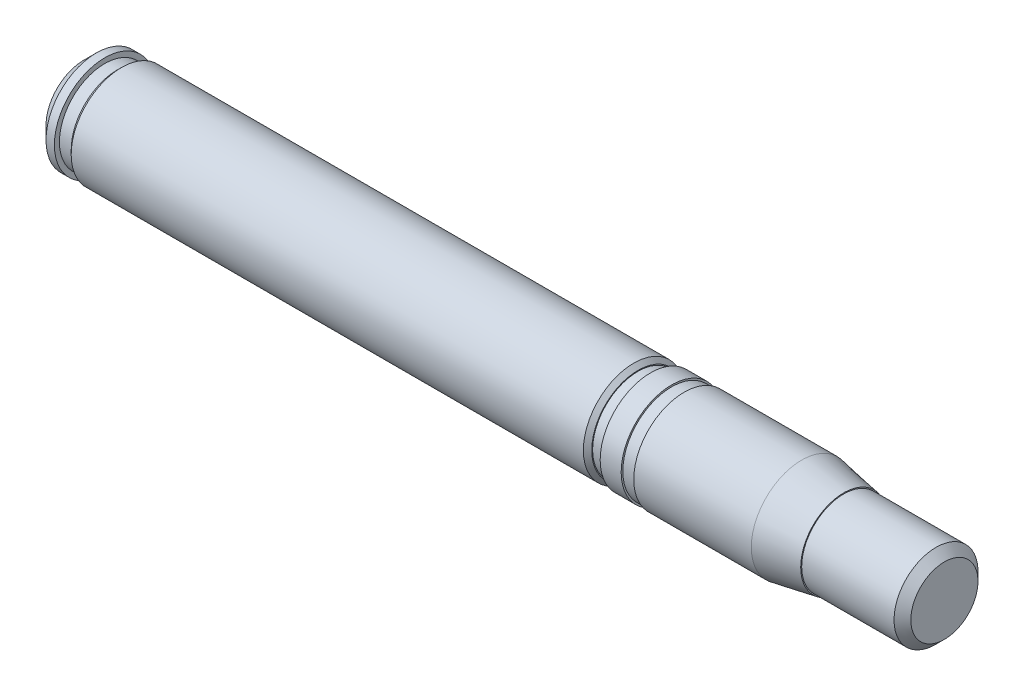
SolidWorks part; units mm, degrees
ref_plane "Plan de face" through (0, 0, 0) normal (0, 0, 1) x (1, 0, 0)
ref_plane "Plan de dessus" through (0, 0, 0) normal (0, 1, 0) x (1, 0, 0)
ref_plane "Plan de droite" through (0, 0, 0) normal (1, 0, 0) x (0, 0, -1)
sketch "Esquisse1" plane through (0, 0, 0) normal (0, 0, 1) x (1, 0, 0)
  line L0 (-77.6743, 0) -> (84.4408, 0) construction
  line L1 (-64.7885, 0) -> (-64.7885, 6)
  line L2 (-64.7885, 6) -> (-62.2885, 6)
  line L3 (-62.2885, 6) -> (-62.2885, 5.4)
  line L4 (-62.2885, 5.4) -> (-60.7885, 5.4)
  line L5 (-60.7885, 5.4) -> (-60.7885, 6)
  line L6 (-60.7885, 6) -> (1.2115, 6)
  line L7 (1.2115, 6) -> (1.2115, 5.4)
  line L8 (1.2115, 5.4) -> (2.7115, 5.4)
  line L9 (2.7115, 5.4) -> (2.7115, 6)
  line L10 (2.7115, 6) -> (5.2115, 6)
  line L11 (5.2115, 5.8) -> (6.7115, 5.8)
  line L12 (6.7115, 5.8) -> (6.7115, 6)
  line L13 (6.7115, 6) -> (20.7115, 6)
  line L14 (20.7115, 6) -> (25.7115, 5.1184)
  line L15 (5.2115, 6) -> (5.2115, 5.8)
  line L16 (25.7115, 5.1184) -> (25.7115, 5)
  line L17 (25.7115, 5) -> (37.7115, 5)
  line L18 (37.7115, 5) -> (37.7115, 0)
  line L19 (-64.7885, 0) -> (37.7115, 0)
  dimension "D1" = 2.5
  dimension "D2" = 1.5
  dimension "D3" = 1.5
  dimension "D4" = 2.5
  dimension "D5" = 1.5
  dimension "D6" = 5
  dimension "D7" = 12
  dimension "D8" = 23
  dimension "D9" = 65
  dimension "D10" = 5
  dimension "D11" = 10
  dimension "D12" = 5.4
  dimension "D13" = 5.4
  dimension "D14" = 5.8
  dimension "D15" = 6
  dimension "D16" = 6
  dimension "D17" = 6
  dimension "D18" = 6
revolve "Révolution1" add sketch "Esquisse1" angle 360 about L0
cosmetic thread "Représentation de filetage1" parameters "D2"=8.5
chamfer "Chanfrein1" distance 1 angle 45 1 edges at (37.7115, 0, 5)
chamfer "Chanfrein2" distance 1.5 angle 45 1 edges at (-64.7885, 0, 6)
chamfer "Chanfrein3" distance 0.5 angle 45 2 edges at (1.2115, 0, 6) (-60.7885, 0, 6)
